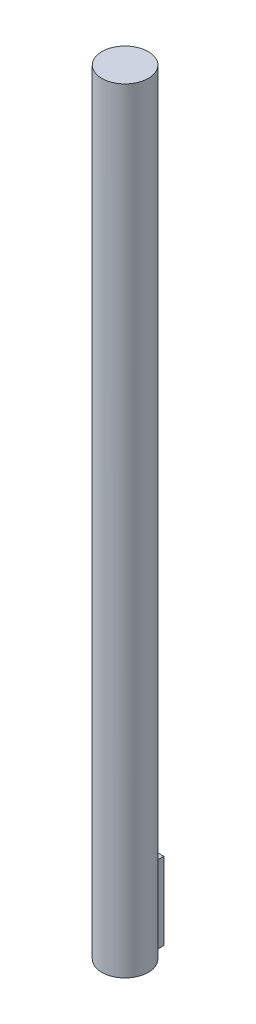
SolidWorks part; units mm, degrees
ref_plane "정면" through (0, 0, 0) normal (0, 0, 1) x (1, 0, 0)
ref_plane "윗면" through (0, 0, 0) normal (0, 1, 0) x (1, 0, 0)
ref_plane "우측면" through (0, 0, 0) normal (1, 0, 0) x (0, 0, -1)
sketch "스케치1" plane through (0, 0, 0) normal (0, 1, 0) x (1, 0, 0)
  circle A0 centre (0, 0) radius 3
  dimension "D1" = 6
extrude "보스-돌출1" add sketch "스케치1" along normal blind 100
sketch "스케치2" plane through (0, 0, 0) normal (0, 1, 0) x (1, 0, 0)
  line L1 (-1, 4) -> (1, 4)
  line L2 (-1, 4) -> (-1, 2)
  line L3 (-1, 2) -> (1, 2)
  line L4 (1, 4) -> (1, 2)
  line L5 (-1, 4) -> (1, 2) construction
  line L6 (-1, 2) -> (1, 4) construction
  circle A0 centre (0, 0) radius 3 construction
  point P0 (0, 3)
  point P7 (0, 2)
  dimension "D1" = 2
  dimension "D2" = 2
extrude "보스-돌출2" add sketch "스케치2" along normal blind 10
